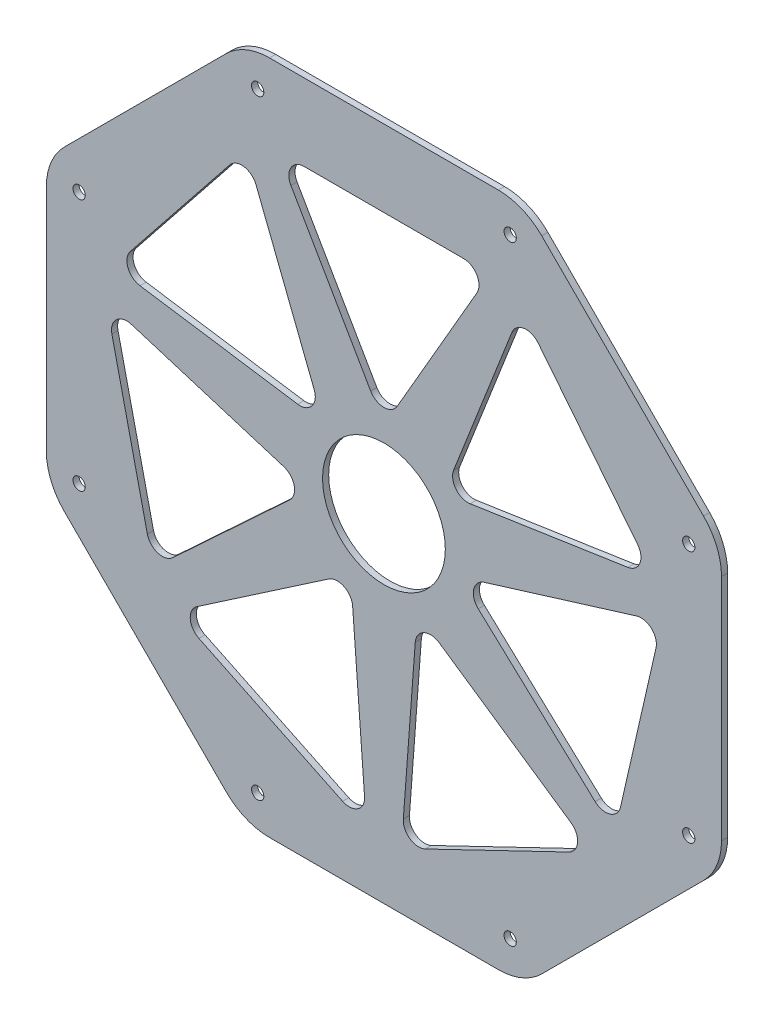
SolidWorks part; units mm, degrees
material "Thornel Mat VMA"
ref_plane "前视基准面" through (0, 0, 0) normal (0, 0, 1) x (1, 0, 0)
ref_plane "上视基准面" through (0, 0, 0) normal (0, 1, 0) x (1, 0, 0)
ref_plane "右视基准面" through (0, 0, 0) normal (1, 0, 0) x (0, 0, -1)
sketch "草图1" plane through (0, 0, 0) normal (0, 0, 1) x (1, 0, 0)
  line L0 (110, 45.5635) -> (-110, -45.5635) construction
  line L1 (110, 45.5635) -> (45.5635, 110)
  line L2 (45.5635, 110) -> (-45.5635, 110)
  line L3 (-45.5635, 110) -> (-110, 45.5635)
  line L4 (-110, 45.5635) -> (-110, -45.5635)
  line L5 (-110, -45.5635) -> (-45.5635, -110)
  line L6 (-45.5635, -110) -> (45.5635, -110)
  line L7 (45.5635, -110) -> (110, -45.5635)
  line L8 (110, -45.5635) -> (110, 45.5635)
  circle A0 centre (0, 0) radius 110 construction
  dimension "D1" = 220
extrude "凸台-拉伸1" add sketch "草图1" along normal blind 2
fillet "圆角1" radius 20 8 edges at (110, -45.5635, 1) (45.5635, -110, 1) (-45.5635, -110, 1) (-110, -45.5635, 1) (-110, 45.5635, 1) (-45.5635, 110, 1) (110, 45.5635, 1) (45.5635, 110, 1)
sketch "草图3" plane through (0, 0, 0) normal (0, 0, -1) x (-1, 0, 0)
  line L0 (0, 0) -> (-108.4776, 44.9329) construction
  circle A0 centre (-99.317, 41.1385) radius 2
  circle A1 centre (0, 0) radius 107.5 construction
  arc A2 (-104.1421, 51.4214) -> (-110, 37.2792) centre (-90, 37.2792) ccw construction
  circle A3 centre (-41.1385, 99.317) radius 2
  circle A4 centre (41.1385, 99.317) radius 2
  circle A5 centre (99.317, 41.1385) radius 2
  circle A6 centre (99.317, -41.1385) radius 2
  circle A7 centre (41.1385, -99.317) radius 2
  circle A8 centre (-41.1385, -99.317) radius 2
  circle A9 centre (-99.317, -41.1385) radius 2
  point P25 (0, 0)
  dimension "D1" = 215
  dimension "D2" = 4
  dimension "D3" = 8
extrude "切除-拉伸2" cut sketch "草图3" against normal blind 10
sketch "草图4" plane through (0, 0, 0) normal (0, 0, -1) x (-1, 0, 0)
  line L0 (0, 0) -> (0, 88.9178) construction
  line L1 (88.054, 25.9132) -> (44.8574, 80.0801)
  line L2 (0, 25) -> (34.641, 85)
  line L3 (34.641, 85) -> (-34.641, 85)
  line L4 (-34.641, 85) -> (0, 25)
  line L5 (44.8574, 80.0801) -> (19.5458, 15.5872)
  line L6 (0, 0) -> (69.5188, 55.4394) construction
  line L7 (19.5458, 15.5872) -> (88.054, 25.9132)
  line L8 (75.1605, -52.6868) -> (90.5772, 14.8582)
  line L9 (90.5772, 14.8582) -> (24.3732, -5.563)
  line L10 (0, 0) -> (86.6885, -19.7861) construction
  line L11 (24.3732, -5.563) -> (75.1605, -52.6868)
  line L12 (5.6696, -91.6125) -> (68.0906, -61.5522)
  line L13 (68.0906, -61.5522) -> (10.8471, -22.5242)
  line L14 (0, 0) -> (38.58, -80.1122) construction
  line L15 (10.8471, -22.5242) -> (5.6696, -91.6125)
  line L16 (-68.0906, -61.5522) -> (-5.6696, -91.6125)
  line L17 (-5.6696, -91.6125) -> (-10.8471, -22.5242)
  line L18 (0, 0) -> (-38.58, -80.1122) construction
  line L19 (-10.8471, -22.5242) -> (-68.0906, -61.5522)
  line L20 (-90.5772, 14.8582) -> (-75.1605, -52.6868)
  line L21 (-75.1605, -52.6868) -> (-24.3732, -5.563)
  line L22 (0, 0) -> (-86.6885, -19.7861) construction
  line L23 (-24.3732, -5.563) -> (-90.5772, 14.8582)
  line L24 (-44.8574, 80.0801) -> (-88.054, 25.9132)
  line L25 (-88.054, 25.9132) -> (-19.5458, 15.5872)
  line L26 (0, 0) -> (-69.5188, 55.4394) construction
  line L27 (-19.5458, 15.5872) -> (-44.8574, 80.0801)
  circle A0 centre (0, 65) radius 20 construction
  circle A1 centre (0, 0) radius 25 construction
  circle A2 centre (50.819, 40.5268) radius 20 construction
  circle A3 centre (63.3703, -14.4639) radius 20 construction
  circle A4 centre (28.2024, -58.563) radius 20 construction
  circle A5 centre (-28.2024, -58.563) radius 20 construction
  circle A6 centre (-63.3703, -14.4639) radius 20 construction
  circle A7 centre (0, 0) radius 20
  circle A8 centre (-50.819, 40.5268) radius 20 construction
  point P37 (0, 0)
  point P49 (0, 0)
  dimension "D1" = 50
  dimension "D2" = 40
  dimension "D4" = 40
extrude "切除-拉伸3" cut sketch "草图4" against normal blind 10
fillet "圆角2" radius 5 21 edges at (34.641, 85, 1) (0, 25, 1) (-24.3732, -5.563, 1) (-90.5772, 14.8582, 1) (-75.1605, -52.6868, 1) (-19.5458, 15.5872, 1) (-44.8574, 80.0801, 1) (-88.054, 25.9132, 1) (19.5458, 15.5872, 1) (88.054, 25.9132, 1) (44.8574, 80.0801, 1) (24.3732, -5.563, 1) (75.1605, -52.6868, 1) (90.5772, 14.8582, 1) (10.8471, -22.5242, 1) (5.6696, -91.6125, 1) (68.0906, -61.5522, 1) (-10.8471, -22.5242, 1) (-68.0906, -61.5522, 1) (-5.6696, -91.6125, 1) (-34.641, 85, 1)
